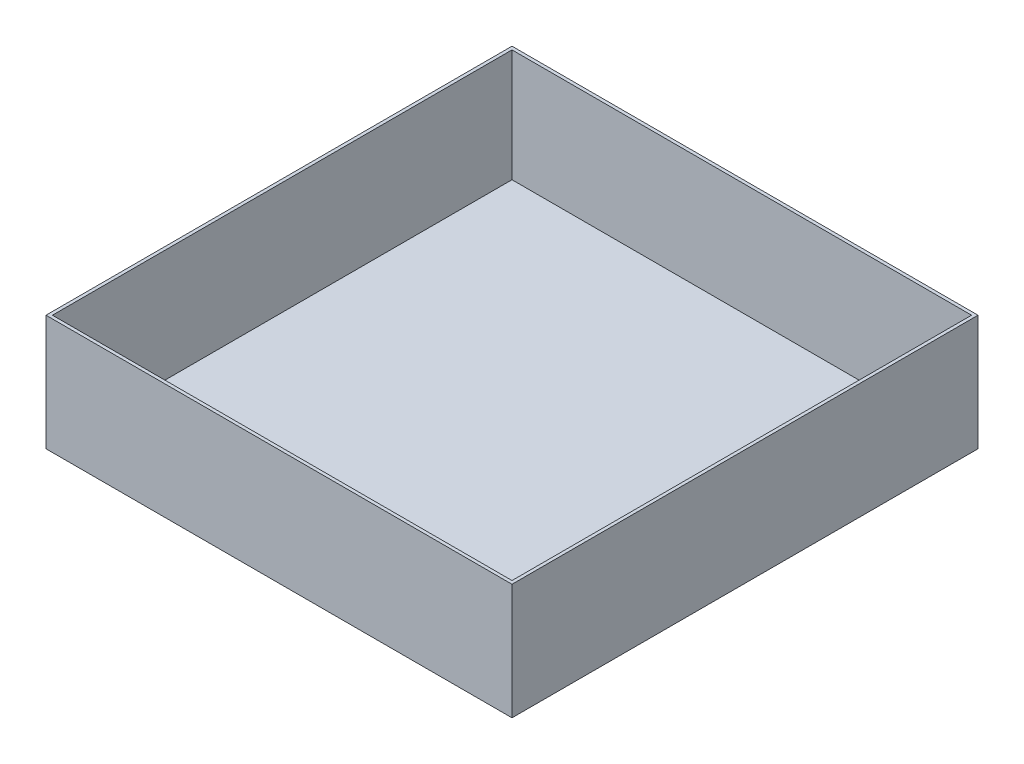
SolidWorks part; units mm, degrees
ref_plane "Front" through (0, 0, 0) normal (0, 0, 1) x (1, 0, 0)
ref_plane "Top" through (0, 0, 0) normal (0, 1, 0) x (1, 0, 0)
ref_plane "Right" through (0, 0, 0) normal (1, 0, 0) x (0, 0, -1)
sketch "Sketch1" plane through (0, 0, 0) normal (0, 1, 0) x (1, 0, 0)
  line L1 (-143, -143) -> (143, -143)
  line L2 (-143, -143) -> (-143, 143)
  line L3 (-143, 143) -> (143, 143)
  line L4 (143, -143) -> (143, 143)
  line L5 (-143, -143) -> (143, 143) construction
  line L6 (-143, 143) -> (143, -143) construction
  line L7 (-145, -145) -> (145, -145)
  line L8 (-145, -145) -> (-145, 145)
  line L9 (-145, 145) -> (145, 145)
  line L10 (145, -145) -> (145, 145)
  line L11 (-145, -145) -> (145, 145) construction
  line L12 (-145, 145) -> (145, -145) construction
  point P0 (0, 0)
  point P6 (0, 0)
  point P11 (0, 0)
  dimension "D1" = 286
  dimension "D2" = 286
  dimension "D3" = 2
  dimension "D4" = 2
extrude "Boss-Extrude1" add sketch "Sketch1" along normal blind 70
sketch "Sketch5" plane through (0, 0, 0) normal (0, -1, 0) x (-1, 0, 0)
  line L1 (145, 145) -> (-145, 145)
  line L2 (145, 145) -> (145, -145)
  line L3 (145, -145) -> (-145, -145)
  line L4 (-145, 145) -> (-145, -145)
  line L5 (145, 145) -> (-145, -145) construction
  line L6 (145, -145) -> (-145, 145) construction
  point P0 (0, 0)
extrude "Boss-Extrude3" add sketch "Sketch5" along normal blind 2
